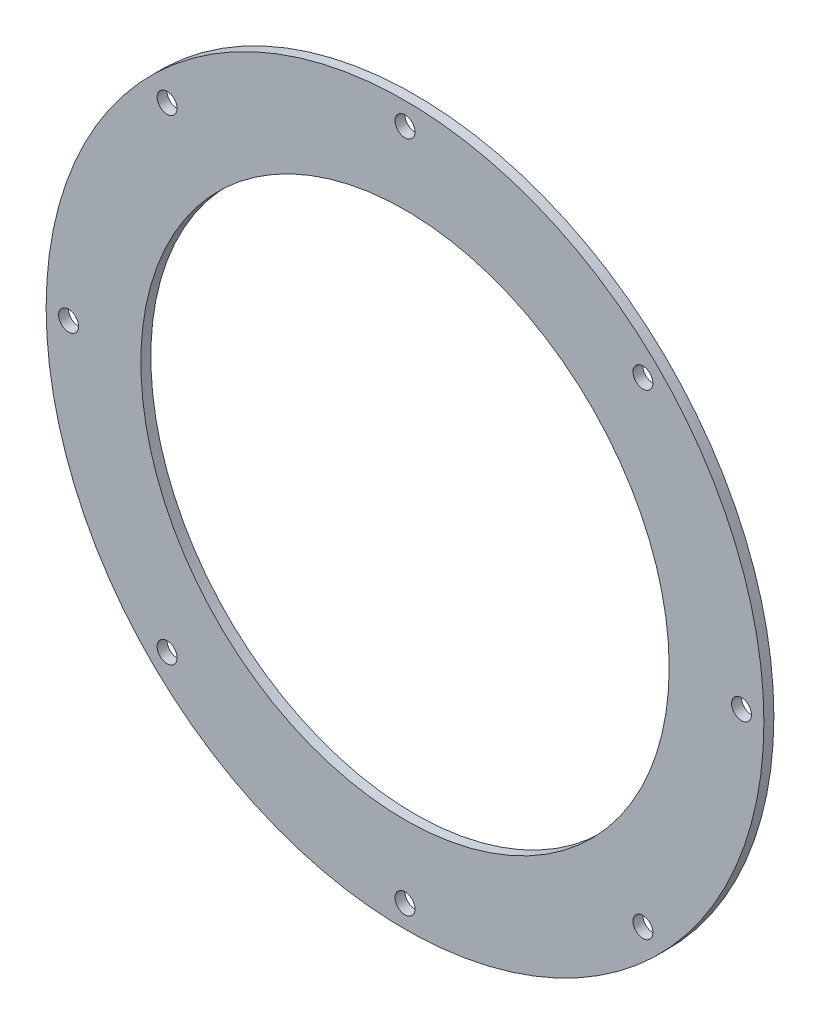
SolidWorks part; units mm, degrees
ref_plane "前视基准面" through (0, 0, 0) normal (0, 0, 1) x (1, 0, 0)
ref_plane "上视基准面" through (0, 0, 0) normal (0, 1, 0) x (1, 0, 0)
ref_plane "右视基准面" through (0, 0, 0) normal (1, 0, 0) x (0, 0, -1)
sketch "草图1" plane through (0, 0, 0) normal (0, 0, 1) x (1, 0, 0)
  circle A0 centre (0, 0) radius 67.5 construction
  circle A1 centre (0, -67.5) radius 2
  circle A2 centre (-47.7297, -47.7297) radius 2
  circle A3 centre (-67.5, 0) radius 2
  circle A4 centre (-47.7297, 47.7297) radius 2
  circle A5 centre (0, 67.5) radius 2
  circle A6 centre (47.7297, 47.7297) radius 2
  circle A7 centre (67.5, 0) radius 2
  circle A8 centre (47.7297, -47.7297) radius 2
  circle A9 centre (0, 0) radius 53
  circle A10 centre (0, 0) radius 72
  dimension "D1" = 135
  dimension "D2" = 8
  dimension "D3" = 144
  dimension "D4" = 106
extrude "凸台-拉伸1" add sketch "草图1" along normal blind 2
